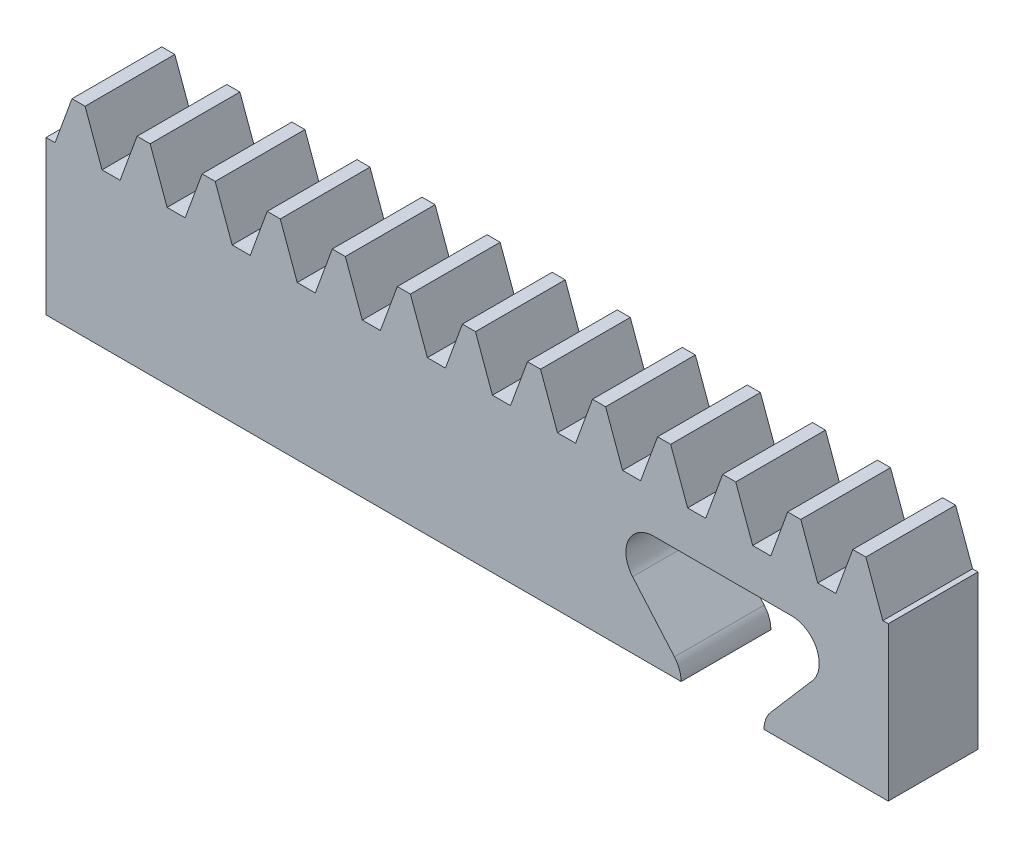
SolidWorks part; units mm, degrees
extrude "Blank" add sketch "BlankSke" against normal blind 6.5
sketch "BlankSke" plane through (0, 0, 0) normal (0, 0, 1) x (1, 0, 0)
  line L1 (0, 0) -> (61, 0)
  line L2 (0, 0) -> (0, 14.5)
  line L3 (0, 14.5) -> (61, 14.5)
  line L4 (61, 0) -> (61, 14.5)
  dimension "Length" = 61
  dimension "Blank_height" = 14.5
ref_plane "Plane1" through (0, 0, 0) normal (0, 0, 1) x (1, 0, 0)
ref_plane "Plane2" through (0, 0, 0) normal (0, 1, 0) x (1, 0, 0)
ref_plane "Plane3" through (0, 0, 0) normal (1, 0, 0) x (0, 0, -1)
other "Configuration Table"
sketch "HoldingSke" plane through (0, 0, 0) normal (0, 1, 0) x (1, 0, 0)
  line L0 (0, 0) -> (0.0928, 0.6602)
  line L1 (-15, 0) -> (100, 0) construction
  line L2 (0, 0) -> (-2.1039, 2.3779)
  line L3 (0, 0) -> (-11.863, 4.5341)
  line L4 (0, 0) -> (8.3795, 2.0892)
  line L5 (0, 0) -> (-23.7986, -8.8762)
  line L6 (0, 0) -> (-10.5278, -7.1032)
  line L9 (-71.009, 38.7566) -> (-13.6877, 59.6198)
  line L10 (-76.2, 3.8779) -> (-63.2, 3.8779)
  line L11 (0, 0) -> (-6.5, 0)
  line L12 (-76.2, 101.6) -> (-76.147, 101.6)
  line L13 (24.9733, 27.94) -> (52.9518, 28.4284)
  line L14 (24.9733, 27.94) -> (24.9743, 27.94)
  line L15 (24.9733, 27.94) -> (100.4006, 29.5858)
  circle A0 centre (0, 0) radius 19.05
  circle A1 centre (0, 0) radius 6.5
  circle A2 centre (0, 0) radius 12.7
  dimension "MPH" = 13
  dimension "Diameter" = 38.1
  dimension "Num_teeth" = 14
  dimension "Pitch" = 0.6667
  dimension "Show_teeth" = 998
  dimension "Thickness" = 12.7
  dimension "Ap" = 20
  dimension "Pitch_height" = 13
  dimension "Width" = 6.5
  dimension "Backlash" = 0.053
  dimension "Addendum_fac" = 1
  dimension "Dedendum_fac" = 1.25
  dimension "Clearance_fac" = 0.25
  dimension "Dedendum_add" = 0.001
  dimension "Length" = 61
  dimension "Module" = 1.5
sketch "TooCutSkeIll" plane through (0, 0, 0) normal (0, 0, 1) x (1, 0, 0)
  line L0 (-1.8687, 14.4605) -> (-0.7447, 11.3724)
  line L1 (-0.3914, 11.125) -> (0.3914, 11.125)
  line L2 (0.7447, 11.3724) -> (1.8687, 14.4605)
  line L3 (61, 14.5) -> (0, 14.5) construction
  line L4 (0, 0) -> (0, 64.897) construction
  line L5 (-13.208, 13) -> (12.954, 13) construction
  line L6 (0, 0) -> (61, 0) construction
  line L7 (1.3371, 13) -> (1.3371, 48.7463) construction
  line L8 (-1.3371, 13) -> (-1.3371, 48.7463) construction
  line L9 (1.9251, 14.5) -> (1.9251, 14.5254)
  line L10 (-1.9251, 14.5) -> (-1.9251, 14.5254)
  line L11 (-1.9251, 14.5254) -> (1.9251, 14.5254)
  arc A0 (0.3914, 11.125) -> (0.7447, 11.3724) centre (0.3914, 11.501) ccw
  arc A1 (-0.7447, 11.3724) -> (-0.3914, 11.125) centre (-0.3914, 11.501) ccw
  arc A2 (1.9251, 14.5) -> (1.8687, 14.4605) centre (1.9251, 14.44) ccw
  arc A3 (-1.8687, 14.4605) -> (-1.9251, 14.5) centre (-1.9251, 14.44) ccw
  dimension "Pitch_height" = 13
  dimension "Addendum_plus" = 1.5254
  dimension "Pressure_angle" = 20
  dimension "Gap_width" = 2.6742
  dimension "Dedendum" = 1.875
extrude "ToothCutIll" [suppressed] cut sketch "TooCutSkeIll" against normal through all
sketch "TooCutSkeSim" plane through (0, 0, 0) normal (0, 0, 1) x (1, 0, 0)
  line L0 (0.6547, 11.125) -> (-0.6547, 11.125)
  line L1 (1.8923, 14.5254) -> (0.6547, 11.125)
  line L2 (0, 17.4625) -> (0, 53.467) construction
  line L3 (1.8923, 14.5254) -> (-1.8923, 14.5254)
  line L6 (-1.8923, 14.5254) -> (-0.6547, 11.125)
  line L9 (-1.3371, 13) -> (1.3371, 13) construction
  line L10 (0, 0) -> (61, 0) construction
  line L11 (1.3371, 13) -> (1.3371, 53.467) construction
  line L12 (-1.3371, 13) -> (-1.3371, 53.467) construction
  dimension "Pitch_height" = 13
  dimension "Addendum_plus" = 1.5254
  dimension "Pressure_angle" = 20
  dimension "Gap_width" = 2.6742
  dimension "Dedendum" = 1.875
extrude "ToothCutSim" cut sketch "TooCutSkeSim" against normal through all
pattern_linear "TeethCuts" count 14 spacing 4.7124 along (1, 0, 0) of "ToothCutIll", "ToothCutSim"
sketch "Sketch1" plane through (0, 0, -6.5) normal (0, 0, -1) x (-1, 0, 0)
  line L0 (-49, 0) -> (-49, 8.8731) construction
  line L1 (0, 0) -> (-61, 0) construction
  line L2 (-44, 8.125) -> (-54, 8.125)
  line L3 (-55.5146, 4.8189) -> (-52.4854, 1.3061)
  line L4 (-42.4854, 4.8189) -> (-45.5146, 1.3061)
  line L5 (-46, 0) -> (-52, 0)
  line L6 (-61, 0) -> (-61, 11.125) construction
  line L7 (-46.4692, 11.125) -> (-47.7785, 11.125) construction
  arc A0 (-54, 8.125) -> (-55.5146, 4.8189) centre (-54, 6.125) ccw
  arc A1 (-44, 8.125) -> (-42.4854, 4.8189) centre (-44, 6.125) cw
  arc A2 (-52, 0) -> (-52.4854, 1.3061) centre (-54, 0) ccw
  arc A3 (-46, 0) -> (-45.5146, 1.3061) centre (-44, 0) cw
  point P7 (-49, 8.125)
  point P16 (0, 0)
  point P17 (-48.9121, 0)
  point P22 (-49, 0)
  dimension "D1" = 2
  dimension "D2" = 2
  dimension "D3" = 10
  dimension "D4" = 12
  dimension "D5" = 6
  dimension "D6" = 3
  dimension "D7" = 8.125
extrude "Cut-Extrude1" cut sketch "Sketch1" against normal up to surface (6.5 mm away) up to face at (30.6212, 12.2946, 0)
equation "' \"Module@HoldingSke\" = 6.35"
equation "' \"Num_teeth@HoldingSke\" = 12"
equation "' \"Ap@HoldingSke\" =  20"
equation "' \"Ap@HoldingSke\" = 20"
equation "' \"Width@HoldingSke\" = 0.25 * 25.4"
equation "' \"Show_teeth@HoldingSke\" = 500"
equation "' \"Backlash@HoldingSke\" = 0.009 * 25.4"
equation "' \"Addendum_fac@HoldingSke\" = 1.0"
equation "' \"Dedendum_fac@HoldingSke\" = 1.25"
equation "' \"Dedendum_add@HoldingSke\" = 0.00005 * 25.4"
equation "' \"Clearance_fac@HoldingSke\" = 0.25"
equation "' \"Pitch_height@HoldingSke\" = 1 * 25.4"
equation "' \"Length@HoldingSke\" = 4.71 * 25.4"
equation "\"Pitch@HoldingSke\" = 1 / \"Module@HoldingSke\""
equation "\"MPH@HoldingSke\" = \"Dedendum_fac@HoldingSke\" / \"Pitch@HoldingSke\" + 2 * \"Dedendum_add@HoldingSke\" + 0.002 * 25.4"
equation "\"MPH@HoldingSke\" = ((sgn( \"MPH@HoldingSke\" - \"Pitch_height@HoldingSke\")+1)*( \"MPH@HoldingSke\" - \"Pitch_height@HoldingSke\"))/2 + \"Pitch_height@HoldingSke\""
equation "\"Blank_height@BlankSke\" = \"Pitch_height@HoldingSke\" + \"Addendum_fac@HoldingSke\"  / \"Pitch@HoldingSke\" "
equation "\"Length@BlankSke\" =  \"Length@HoldingSke\""
equation "\"Face_width@Blank\" = \"Width@HoldingSke\""
equation "\"Pressure_angle@TooCutSkeIll\" = \"Ap@HoldingSke\""
equation "\"Addendum_plus@TooCutSkeIll\" =  \"Addendum_fac@HoldingSke\"  / \"Pitch@HoldingSke\" + 0.001 *25.4"
equation "\"Dedendum@TooCutSkeIll\" = \"Dedendum_fac@HoldingSke\"  / \"Pitch@HoldingSke\""
equation "\"Pitch_height@TooCutSkeIll\" =  \"MPH@HoldingSke\""
equation "\"Gap_width@TooCutSkeIll\" = 3.14159265 / 2 / \"Pitch@HoldingSke\" + 6 * \"Backlash@HoldingSke\""
equation "\"Pressure_angle@TooCutSkeSim\" = \"Ap@HoldingSke\""
equation "\"Addendum_plus@TooCutSkeSim\" =  \"Addendum_fac@HoldingSke\"  / \"Pitch@HoldingSke\" + 0.001 * 25.4"
equation "\"Dedendum@TooCutSkeSim\" = \"Dedendum_fac@HoldingSke\"  / \"Pitch@HoldingSke\""
equation "\"Pitch_height@TooCutSkeSim\" =  \"MPH@HoldingSke\""
equation "\"Gap_width@TooCutSkeSim\" = 3.14159265 / 2 / \"Pitch@HoldingSke\" + 6 * \"Backlash@HoldingSke\""
equation "\"Root_fillet@TooCutSkeIll\" = \"Clearance_fac@HoldingSke\" / \"Pitch@HoldingSke\" + \"Dedendum_add@HoldingSke\""
equation "\"Break_rad@TooCutSkeIll\" = 0.02 / \"Pitch@HoldingSke\" * 2"
equation "\"Linear_pitch@TeethCuts\" = 3.14159265 / \"Pitch@HoldingSke\""
equation "\"Num_teeth@HoldingSke\" = int( ( \"Length@HoldingSke\" + 0 ) / (3.14159265 / \"Pitch@HoldingSke\")) + 0.9999  + 1"
equation " \"Num_teeth@TeethCuts\" = int( \"Show_teeth@HoldingSke\" ) + 1"
equation " \"Num_teeth@TeethCuts\" = ((sgn( \"Num_teeth@TeethCuts\" - \"Num_teeth@HoldingSke\" )-1)*( \"Num_teeth@TeethCuts\" - \"Num_teeth@HoldingSke\" ))/-2+ \"Num_teeth@HoldingSke\""
equation " \"Num_teeth@TeethCuts\" = ((sgn( \"Num_teeth@TeethCuts\" - 2.0)+1)*( \"Num_teeth@TeethCuts\" - 2.0))/2 +2.0"
